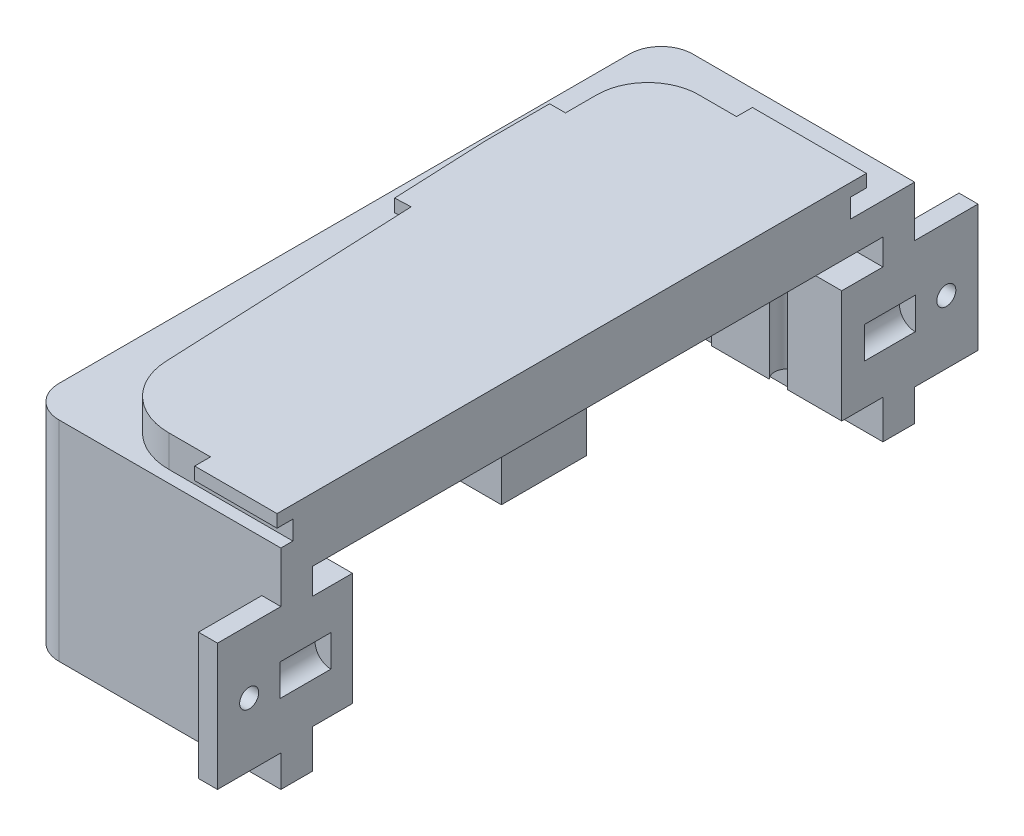
SolidWorks part; units mm, degrees
ref_plane "Front Plane" through (0, 0, 0) normal (0, 0, 1) x (1, 0, 0)
ref_plane "Top Plane" through (0, 0, 0) normal (0, 1, 0) x (1, 0, 0)
ref_plane "Right Plane" through (0, 0, 0) normal (1, 0, 0) x (0, 0, -1)
sketch "Sketch1" plane through (0, 0, 0) normal (0, 1, 0) x (1, 0, 0)
  line L0 (-32, 36) -> (-32, 21)
  line L3 (-24, 44) -> (24, 44)
  line L7 (32, 36) -> (32, 21)
  line L8 (-32, 21) -> (-29.5796, -34.4362)
  line L9 (-19.5891, -44) -> (19.5891, -44)
  line L10 (29.5796, -34.4362) -> (32, 21)
  line L11 (-24, 41) -> (24, 41)
  line L12 (29, 36) -> (29, 21.0655)
  line L13 (26.5825, -34.3053) -> (29, 21.0655)
  line L14 (-19.5891, -41) -> (19.5891, -41)
  line L15 (-29, 21.0655) -> (-26.5825, -34.3053)
  line L16 (-29, 36) -> (-29, 21.0655)
  line L17 (-35, -45.9) -> (35, -45.9)
  line L18 (-40, -40.9) -> (-40, 49.1)
  line L19 (-35, 54.1) -> (35, 54.1)
  line L20 (40, -40.9) -> (40, 49.1)
  arc A2 (-19.5891, -44) -> (-29.5796, -34.4362) centre (-19.5891, -34) cw
  arc A3 (29.5796, -34.4362) -> (19.5891, -44) centre (19.5891, -34) cw
  arc A4 (-24, 44) -> (-32, 36) centre (-24, 36) ccw
  arc A5 (32, 36) -> (24, 44) centre (24, 36) ccw
  arc A6 (29, 36) -> (24, 41) centre (24, 36) ccw
  arc A7 (26.5825, -34.3053) -> (19.5891, -41) centre (19.5891, -34) cw
  arc A8 (-19.5891, -41) -> (-26.5825, -34.3053) centre (-19.5891, -34) cw
  arc A9 (-24, 41) -> (-29, 36) centre (-24, 36) ccw
  arc A10 (-40, -40.9) -> (-35, -45.9) centre (-35, -40.9) ccw
  arc A11 (35, -45.9) -> (40, -40.9) centre (35, -40.9) ccw
  arc A12 (40, 49.1) -> (35, 54.1) centre (35, 49.1) ccw
  arc A13 (-35, 54.1) -> (-40, 49.1) centre (-35, 49.1) ccw
  point P0 (0, 0)
  point P32 (0, 4.1)
  dimension "D1" = 177.5
  dimension "D4" = 8
  dimension "D5" = 8
  dimension "D8" = 15
  dimension "D13" = 10
  dimension "D14" = 10
  dimension "D12" = 5
  dimension "D2" = 44
  dimension "D3" = 177.5
  dimension "D6" = 32
  dimension "D7" = 32
  dimension "D9" = 15
  dimension "D10" = 44
  dimension "D11" = 3
  dimension "D15" = 100
  dimension "D16" = 80
  dimension "D17" = 50
  dimension "D18" = 40
  dimension "D19" = 4.1
ref_plane "Plane1" through (0, 25, 0) normal (0, 1, 0) x (1, 0, 0)
sketch "Sketch8" plane through (0, 0, 0) normal (0, 1, 0) x (-1, 0, 0)
  line L0 (32, -36) -> (32, -21)
  line L1 (24, -44) -> (-24, -44)
  line L2 (-32, -36) -> (-32, -21)
  line L3 (32, -21) -> (29.5796, 34.4362)
  line L4 (19.5891, 44) -> (-19.5891, 44)
  line L5 (-29.5796, 34.4362) -> (-32, -21)
  line L7 (15.9, 11.8) -> (-15.9, -20) construction
  line L9 (-15.9, 11.8) -> (15.9, -20) construction
  arc A0 (19.5891, 44) -> (29.5796, 34.4362) centre (19.5891, 34) cw
  arc A1 (-29.5796, 34.4362) -> (-19.5891, 44) centre (-19.5891, 34) cw
  arc A2 (24, -44) -> (32, -36) centre (24, -36) ccw
  arc A3 (-32, -36) -> (-24, -44) centre (-24, -36) ccw
  circle A4 centre (15.9, 11.8) radius 10
  circle A8 centre (-15.9, 11.8) radius 10
  circle A9 centre (15.9, -20) radius 10
  circle A10 centre (-15.9, -20) radius 10
  point P0 (0, 0)
  point P28 (0, -4.1)
  dimension "D7" = 10
  dimension "D8" = 10
  dimension "D9" = 8
  dimension "D10" = 8
  dimension "D13" = 20
  dimension "D14" = 24
  dimension "D20" = 20
  dimension "D21" = 20
  dimension "D22" = 20
  dimension "D1" = 44
  dimension "D2" = 177.5
  dimension "D3" = 177.5
  dimension "D4" = 32
  dimension "D5" = 32
  dimension "D6" = 44
  dimension "D11" = 15
  dimension "D12" = 15
  dimension "D15" = 31.8
  dimension "D16" = 31.8
  dimension "D17" = 31.8
  dimension "D18" = 31.8
  dimension "D19" = 15.9
  dimension "D23" = 4.1
extrude "Boss-Extrude6" add sketch "Sketch8" against normal blind 5 separate body
extrude "Boss-Extrude7" add sketch "Sketch1" along normal blind 5 contours L19 A13 L18 A10 L17 A11 L20 A12 A5 L7 L10 A3 L9 A2 L8 L0 A4 L3 | L7 A5 L3 A4 L0 L8 A2 L9 A3 L10 A9 L11 A6 L12 L13 A7 L14 A8 L15 L16
ref_plane "Plane2" through (0, 38, 0) normal (0, 1, 0) x (1, 0, 0)
sketch "Sketch2" plane through (0, 25, 0) normal (0, 1, 0) x (1, 0, 0)
  line L1 (-35, -45.9) -> (35, -45.9)
  line L2 (-40, -40.9) -> (-40, 49.1)
  line L3 (-35, 54.1) -> (35, 54.1)
  line L4 (40, -40.9) -> (40, 49.1)
  arc A0 (-40, -40.9) -> (-35, -45.9) centre (-35, -40.9) ccw
  arc A1 (35, -45.9) -> (40, -40.9) centre (35, -40.9) ccw
  arc A2 (40, 49.1) -> (35, 54.1) centre (35, 49.1) ccw
  arc A3 (-35, 54.1) -> (-40, 49.1) centre (-35, 49.1) ccw
  point P0 (0, 4.1)
  dimension "D3" = 5
  dimension "D1" = 100
  dimension "D2" = 80
  dimension "D4" = 50
  dimension "D5" = 40
  dimension "D6" = 4.1
extrude "Extrude-Thin4" add sketch "Sketch2" against normal up to surface (20 mm away) and the other way blind 8 separate body thin contours L3 A2 L4 A1 L1 A0 L2 A3
sketch "Sketch10" plane through (0, 38, 0) normal (0, 1, 0) x (1, 0, 0)
  line L0 (-32, 36) -> (-32, 21)
  line L1 (-24, 44) -> (24, 44)
  line L2 (32, 36) -> (32, 21)
  line L3 (-32, 21) -> (-29.5796, -34.4362)
  line L4 (-19.5891, -44) -> (19.5891, -44)
  line L5 (29.5796, -34.4362) -> (32, 21)
  arc A0 (-19.5891, -44) -> (-29.5796, -34.4362) centre (-19.5891, -34) cw
  arc A1 (29.5796, -34.4362) -> (19.5891, -44) centre (19.5891, -34) cw
  arc A2 (-24, 44) -> (-32, 36) centre (-24, 36) ccw
  arc A3 (32, 36) -> (24, 44) centre (24, 36) ccw
  point P0 (0, 0)
  dimension "D7" = 10
  dimension "D8" = 10
  dimension "D9" = 8
  dimension "D10" = 8
  dimension "D1" = 44
  dimension "D2" = 177.5
  dimension "D3" = 177.5
  dimension "D4" = 32
  dimension "D5" = 32
  dimension "D6" = 44
  dimension "D11" = 15
  dimension "D12" = 15
extrude "Boss-Extrude8" add sketch "Sketch10" along normal blind 5 separate body
sketch "Sketch11" plane through (0, 38, 0) normal (0, 1, 0) x (1, 0, 0)
  line L0 (-35, -45.9) -> (35, -45.9)
  line L1 (-40, -40.9) -> (-40, 49.1)
  line L2 (-35, 54.1) -> (35, 54.1)
  line L3 (40, -40.9) -> (40, 49.1)
  line L4 (-35, 54.1) -> (35, 54.1) construction
  line L5 (40, -40.9) -> (40, 49.1) construction
  line L6 (-35, -45.9) -> (35, -45.9) construction
  arc A0 (-40, -40.9) -> (-35, -45.9) centre (-35, -40.9) ccw
  arc A1 (35, -45.9) -> (40, -40.9) centre (35, -40.9) ccw
  arc A2 (40, 49.1) -> (35, 54.1) centre (35, 49.1) ccw
  arc A3 (-35, 54.1) -> (-40, 49.1) centre (-35, 49.1) ccw
  dimension "D1" = 5
extrude "Boss-Extrude9" add sketch "Sketch11" against normal blind 5
sketch "Sketch13" plane through (0, 0, 0) normal (1, 0, 0) x (0, 0, -1)
  line L1 (49.1, 11.1) -> (42.6, 11.1)
  line L2 (49.1, 11.1) -> (49.1, 28.9)
  line L3 (49.1, 28.9) -> (42.6, 28.9)
  line L4 (42.6, 11.1) -> (42.6, 28.9)
  line L5 (-34.6, 11.1) -> (-40.9, 11.1)
  line L6 (-34.6, 11.1) -> (-34.6, 28.9)
  line L7 (-34.6, 28.9) -> (-40.9, 28.9)
  line L8 (-40.9, 11.1) -> (-40.9, 28.9)
  line L9 (-40.9, 33) -> (-40.9, 5) construction
  line L10 (49.1, 33) -> (49.1, 5) construction
  dimension "D1" = 17.8
  dimension "D2" = 6.5
  dimension "D3" = 11.1
  dimension "D4" = 17.8
  dimension "D5" = 6.3
  dimension "D6" = 11.1
extrude "Boss-Extrude10" add sketch "Sketch13" along normal through all and the other way through all
sketch "Sketch15" plane through (0, 11.1, 0) normal (0, -1, 0) x (1, 0, 0)
  line L0 (35, -49.1) -> (-35, -49.1) construction
  line L1 (-35, -42.6) -> (-35, -49.1) construction
  line L3 (-35, 40.9) -> (-35, 34.6) construction
  line L4 (-35, 40.9) -> (35, 40.9) construction
  line L6 (0, -26.4) -> (0, 26.4) construction
  circle A0 centre (-22, -44) radius 2
  circle A1 centre (-10, -44) radius 2
  circle A2 centre (-22, 36) radius 2
  circle A3 centre (-10, 36) radius 2
  circle A4 centre (10, 36) radius 2
  circle A5 centre (22, 36) radius 2
  circle A6 centre (10, -44) radius 2
  circle A7 centre (22, -44) radius 2
  dimension "D1" = 5.1
  dimension "D2" = 4
  dimension "D5" = 4
  dimension "D6" = 4
  dimension "D8" = 4
  dimension "D3" = 13
  dimension "D4" = 12
  dimension "D7" = 12
  dimension "D9" = 4.9
  dimension "D10" = 13
extrude "Cut-Extrude1" cut sketch "Sketch15" against normal up to surface (17.8 mm away) contours A5
sketch "Sketch17" plane through (0, -5, 0) normal (0, 1, 0) x (1, 0, 0)
  line L0 (0, 0) -> (0, 54.1) construction
  line L5 (18, 46.5) -> (18, 43.5)
  line L6 (18, 46.5) -> (-18, 46.5)
  line L7 (18, 43.5) -> (-18, 43.5)
  line L8 (-18, 46.5) -> (-18, 43.5)
  line L9 (18, 46.5) -> (-18, 43.5) construction
  line L10 (18, 43.5) -> (-18, 46.5) construction
  line L11 (-35, 54.1) -> (35, 54.1) construction
  line L12 (-13, -46.5) -> (13, -46.5)
  line L13 (-13, -46.5) -> (-13, -43.5)
  line L14 (-13, -43.5) -> (13, -43.5)
  line L15 (13, -46.5) -> (13, -43.5)
  line L16 (-13, -46.5) -> (13, -43.5) construction
  line L17 (-13, -43.5) -> (13, -46.5) construction
  line L19 (-31.5, 21.0109) -> (-30.8457, 6.0252)
  line L21 (-30.8457, 6.0252) -> (-33.8429, 5.8943)
  line L22 (-33.8429, 5.8943) -> (-34.5, 20.9454)
  line L24 (-34.5, 31.0109) -> (-34.5, 20.9454)
  line L25 (-31.5, 31.0109) -> (-34.5, 31.0109)
  line L27 (24, 44) -> (-24, 44) construction
  line L31 (29.0801, -34.4144) -> (31.5, 21.0109) construction
  line L32 (31.5, 21.0109) -> (31.5, 31.0109) construction
  line L33 (-31.5, 21.0109) -> (-31.5, 31.0109)
  line L40 (31.5, 21.0109) -> (31.5, 31.0109)
  line L41 (31.5, 31.0109) -> (34.5, 31.0109)
  line L46 (34.5, 31.0109) -> (34.5, 20.9454)
  line L47 (31.5, 21.0109) -> (30.8457, 6.0252)
  line L48 (30.8457, 6.0252) -> (33.8429, 5.8943)
  line L49 (33.8429, 5.8943) -> (34.5, 20.9454)
  point P1 (0, 45)
  point P3 (0, -45)
  dimension "D1" = 36
  dimension "D2" = 3
  dimension "D3" = 3
  dimension "D4" = 26
  dimension "D5" = 0.5
  dimension "D7" = 3
  dimension "D8" = 3
  dimension "D12" = 10
  dimension "D13" = 15
sketch "Sketch18" plane through (0, 43, 0) normal (0, 1, 0) x (1, 0, 0)
  line L5 (18, 46.5) -> (18, 43.5)
  line L6 (18, 46.5) -> (-18, 46.5)
  line L7 (18, 43.5) -> (-18, 43.5)
  line L8 (-18, 46.5) -> (-18, 43.5)
  line L9 (18, 46.5) -> (-18, 43.5) construction
  line L10 (18, 43.5) -> (-18, 46.5) construction
  line L12 (-13, -46.5) -> (13, -46.5)
  line L13 (-13, -46.5) -> (-13, -43.5)
  line L14 (-13, -43.5) -> (13, -43.5)
  line L15 (13, -46.5) -> (13, -43.5)
  line L16 (-13, -46.5) -> (13, -43.5) construction
  line L17 (-13, -43.5) -> (13, -46.5) construction
  line L19 (-31.5, 21.0109) -> (-30.8457, 6.0252)
  line L21 (-30.8457, 6.0252) -> (-33.8429, 5.8943)
  line L22 (-33.8429, 5.8943) -> (-34.5, 20.9454)
  line L24 (-34.5, 31.0109) -> (-34.5, 20.9454)
  line L25 (-31.5, 31.0109) -> (-34.5, 31.0109)
  line L31 (29.0801, -34.4144) -> (31.5, 21.0109) construction
  line L32 (31.5, 21.0109) -> (31.5, 31.0109) construction
  line L33 (-31.5, 21.0109) -> (-31.5, 31.0109)
  line L40 (31.5, 21.0109) -> (31.5, 31.0109)
  line L41 (31.5, 31.0109) -> (34.5, 31.0109)
  line L46 (34.5, 31.0109) -> (34.5, 20.9454)
  line L47 (31.5, 21.0109) -> (30.8457, 6.0252)
  line L48 (30.8457, 6.0252) -> (33.8429, 5.8943)
  line L49 (33.8429, 5.8943) -> (34.5, 20.9454)
  point P1 (0, 45)
  point P3 (0, -45)
  dimension "D1" = 36
  dimension "D2" = 3
  dimension "D3" = 3
  dimension "D4" = 26
  dimension "D7" = 3
  dimension "D8" = 3
  dimension "D12" = 10
  dimension "D13" = 15
extrude "Boss-Extrude11" add sketch "Sketch17" along normal blind 2
extrude "Boss-Extrude12" add sketch "Sketch18" against normal blind 2
ref_plane "Plane6" through (0, 5, 0) normal (0, 1, 0) x (1, 0, 0)
sketch "Sketch19" plane through (0, 0, 0) normal (1, 0, 0) x (0, 0, -1)
  line L0 (-45.9, 30) -> (-55.9, 30)
  line L1 (64.1, 30) -> (54.1, 30)
  line L2 (64.1, 30) -> (64.1, 10)
  line L3 (64.1, 10) -> (54.1, 10)
  line L4 (54.1, 30) -> (54.1, 10)
  line L5 (64.1, 30) -> (54.1, 10) construction
  line L6 (64.1, 10) -> (54.1, 30) construction
  line L7 (-45.9, 30) -> (-45.9, 10)
  line L8 (-45.9, 10) -> (-55.9, 10)
  line L9 (-55.9, 30) -> (-55.9, 10)
  line L10 (-45.9, 30) -> (-55.9, 10) construction
  line L11 (-45.9, 10) -> (-55.9, 30) construction
  circle A0 centre (59.1, 20) radius 1.5
  circle A1 centre (-50.9, 20) radius 1.5
  point P0 (59.1, 20)
  point P9 (-50.9, 20)
  dimension "D5" = 3
  dimension "D6" = 3
  dimension "D1" = 54.1
  dimension "D2" = 10
  dimension "D3" = 20
  dimension "D4" = 10
  dimension "D7" = 45.9
  dimension "D8" = 10
  dimension "D9" = 20
  dimension "D10" = 10
extrude "Boss-Extrude13" add sketch "Sketch19" along normal blind 3 and the other way blind 3
ref_plane "Plane7" through (0, 0, 38) normal (0, 0, 1) x (1, 0, 0)
sketch "Sketch21" plane through (0, 0, 38) normal (0, 0, 1) x (1, 0, 0)
  circle A0 centre (0, 20) radius 2.5
  dimension "D1" = 5
  dimension "D2" = 20
ref_plane "Plane8" through (0, 0, -46.2) normal (0, 0, 1) x (1, 0, 0)
sketch "Sketch23" plane through (0, 0, -46.2) normal (0, 0, 1) x (1, 0, 0)
  circle A0 centre (0, 20) radius 2.5
  dimension "D1" = 5
  dimension "D2" = 20
extrude "Cut-Extrude5" cut sketch "Sketch21" along normal blind 8
extrude "Cut-Extrude6" cut sketch "Sketch23" against normal blind 8
sketch "Sketch24" plane through (0, 5, 0) normal (0, 1, 0) x (1, 0, 0)
  line L1 (75, -75) -> (-75, -75)
  line L2 (75, -75) -> (75, 75)
  line L3 (75, 75) -> (-75, 75)
  line L4 (-75, -75) -> (-75, 75)
  line L5 (75, -75) -> (-75, 75) construction
  line L6 (75, 75) -> (-75, -75) construction
  point P0 (0, 0)
extrude "Cut-Extrude7" cut sketch "Sketch24" against normal through all
sketch "Sketch25" plane through (0, 0, 0) normal (1, 0, 0) x (0, 0, -1)
  line L1 (-75, -75) -> (75, -75)
  line L2 (-75, -75) -> (-75, 75)
  line L3 (-75, 75) -> (75, 75)
  line L4 (75, -75) -> (75, 75)
  line L5 (-75, -75) -> (75, 75) construction
  line L6 (-75, 75) -> (75, -75) construction
  point P0 (0, 0)
extrude "Cut-Extrude8" cut sketch "Sketch25" along normal through all
sketch "Sketch26" plane through (0, 11.1, 0) normal (0, -1, 0) x (1, 0, 0)
  line L0 (-23.4283, 34.6) -> (-35, 34.6) construction
  line L1 (-35, 40.9) -> (-28.7, 40.9)
  line L2 (-35, 40.9) -> (-35, 34.6)
  line L3 (-35, 34.6) -> (-28.7, 34.6)
  line L4 (-28.7, 40.9) -> (-28.7, 34.6)
  line L5 (-23.4283, -42.6) -> (-35, -42.6) construction
  line L6 (-35, -49.1) -> (-28.5, -49.1)
  line L7 (-35, -49.1) -> (-35, -42.6)
  line L8 (-35, -42.6) -> (-28.5, -42.6)
  line L9 (-28.5, -49.1) -> (-28.5, -42.6)
extrude "Boss-Extrude14" add sketch "Sketch26" along normal up to surface (6.1 mm away) up to face at (-22.2071, 5, -4.1)
sketch "Sketch27" plane through (0, 5, 0) normal (0, -1, 0) x (1, 0, 0)
  line L0 (-40, -49.1) -> (-40, 40.9) construction
  line L3 (0, 45.9) -> (-35, 45.9) construction
  line L4 (0, -54.1) -> (-35, -54.1) construction
  circle A0 centre (-35, 40.9) radius 2
  circle A1 centre (-35, -49.1) radius 2
  dimension "D1" = 4
  dimension "D4" = 4
  dimension "D2" = 5
  dimension "D3" = 5
  dimension "D5" = 5
  dimension "D6" = 5
extrude "Cut-Extrude9" cut sketch "Sketch27" against normal blind 8
sketch "Sketch28" plane through (0, 33, 0) normal (0, -1, 0) x (1, 0, 0)
  line L0 (-35, 40.9) -> (0, 40.9) construction
  line L1 (-23.5, -10.8) -> (-8.5, -10.8)
  line L2 (-23.5, -10.8) -> (-23.5, 2.6)
  line L3 (-23.5, 2.6) -> (-8.5, 2.6)
  line L4 (-8.5, -10.8) -> (-8.5, 2.6)
  line L5 (-23.5, -10.8) -> (-8.5, 2.6) construction
  line L6 (-23.5, 2.6) -> (-8.5, -10.8) construction
  line L7 (-35, -49.1) -> (0, -49.1) construction
  line L8 (-35, 40.9) -> (-35, -49.1) construction
  point P0 (-16, -4.1)
  dimension "D1" = 38.3
  dimension "D2" = 38.3
  dimension "D3" = 19
  dimension "D4" = 15
extrude "Boss-Extrude15" add sketch "Sketch28" along normal blind 15
sketch "Sketch29" plane through (0, 0, 0) normal (1, 0, 0) x (0, 0, -1)
  circle A0 centre (-21, 12) radius 5
  circle A1 centre (29, 12) radius 5
  dimension "D1" = 21
  dimension "D5" = 10
  dimension "D6" = 10
  dimension "D2" = 29
  dimension "D3" = 12
  dimension "D4" = 12
extrude "Cut-Extrude10" cut sketch "Sketch29" against normal through all and the other way through all
